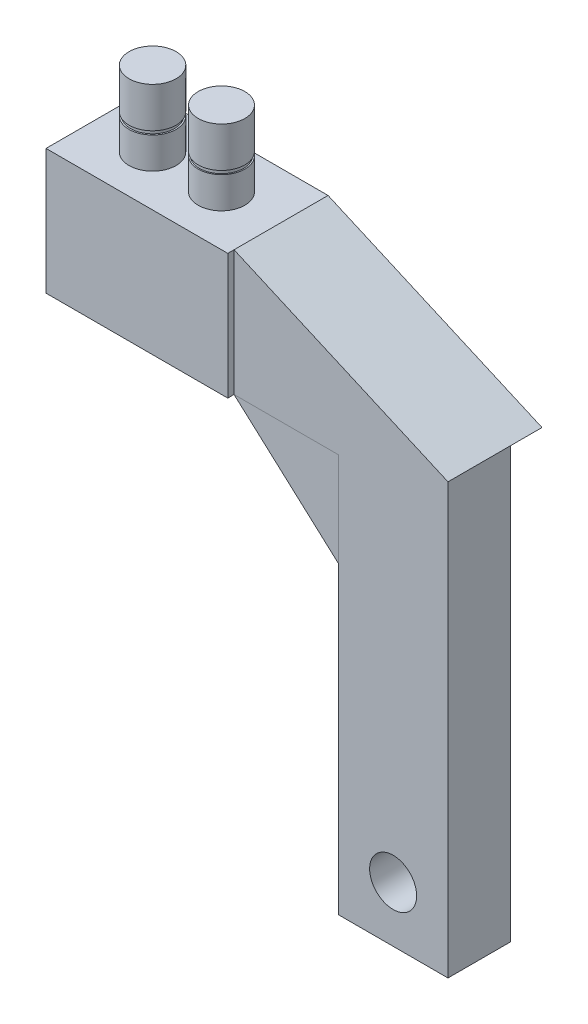
SolidWorks part; units mm, degrees
ref_plane "Front Plane" through (0, 0, 0) normal (0, 0, 1) x (1, 0, 0)
ref_plane "Top Plane" through (0, 0, 0) normal (0, 1, 0) x (1, 0, 0)
ref_plane "Right Plane" through (0, 0, 0) normal (1, 0, 0) x (0, 0, -1)
sketch "Sketch1" plane through (0, 0, 0) normal (0, 1, 0) x (1, 0, 0)
  line L1 (18.415, -10.16) -> (-18.415, -10.16)
  line L2 (18.415, -10.16) -> (18.415, 10.16)
  line L3 (18.415, 10.16) -> (-18.415, 10.16)
  line L4 (-18.415, -10.16) -> (-18.415, 10.16)
  line L5 (18.415, -10.16) -> (-18.415, 10.16) construction
  line L6 (18.415, 10.16) -> (-18.415, -10.16) construction
  point P0 (0, 0)
  dimension "D1" = 36.83
  dimension "D2" = 20.32
extrude "Boss-Extrude1" add sketch "Sketch1" against normal blind 25.4
sketch "Sketch2" plane through (18.415, 0, 0) normal (1, 0, 0) x (0, 0, -1)
  line L0 (-10.16, -25.4) -> (10.16, -25.4) construction
  line L1 (-8.89, -25.4) -> (3.81, -25.4)
  line L2 (-8.89, -25.4) -> (-8.89, -19.05)
  line L3 (-8.89, -19.05) -> (3.81, -19.05)
  line L4 (3.81, -25.4) -> (3.81, -19.05)
  line L5 (-10.16, -25.4) -> (-10.16, 0) construction
  dimension "D1" = 12.7
  dimension "D2" = 6.35
  dimension "D3" = 1.27
extrude "Boss-Extrude2" add sketch "Sketch2" along normal blind 43.3442
sketch "Sketch3" plane through (0, -25.4, 0) normal (0, -1, 0) x (-1, 0, 0)
  line L0 (-61.7592, 3.81) -> (-18.415, 3.81) construction
  line L1 (-61.7592, -8.89) -> (-39.5342, -8.89)
  line L2 (-61.7592, -8.89) -> (-61.7592, 3.81)
  line L3 (-61.7592, 3.81) -> (-39.5342, 3.81)
  line L4 (-39.5342, -8.89) -> (-39.5342, 3.81)
  dimension "D1" = 22.225
extrude "Boss-Extrude3" add sketch "Sketch3" along normal blind 80.7135
sketch "Sketch4" plane through (0, 0, 8.89) normal (0, 0, 1) x (1, 0, 0)
  line L0 (61.7592, -106.1135) -> (39.5342, -106.1135) construction
  line L1 (39.5342, -106.1135) -> (39.5342, -25.4) construction
  circle A0 centre (50.6467, -94.8842) radius 4.7625
  point P4 (0, 0)
  dimension "D1" = 11.2293
  dimension "D2" = 9.525
  dimension "D3" = 11.1125
extrude "Cut-Extrude1" cut sketch "Sketch4" against normal through all
sketch "Sketch5" plane through (0, 0, 0) normal (0, 1, 0) x (1, 0, 0)
  line L0 (-18.415, 10.16) -> (-18.415, -10.16) construction
  line L1 (18.415, 10.16) -> (-18.415, 10.16) construction
  line L2 (18.415, -10.16) -> (18.415, 10.16) construction
  circle A0 centre (-6.985, 0) radius 4.7625
  circle A1 centre (6.985, 0) radius 4.7294
  dimension "D1" = 11.43
  dimension "D3" = 9.525
  dimension "D5" = 9.4588
  dimension "D2" = 10.16
  dimension "D4" = 11.43
  dimension "D6" = 10.16
extrude "Boss-Extrude4" add sketch "Sketch5" along normal blind 15.24
sketch "Sketch7" plane through (0, 0, 10.16) normal (0, 0, 1) x (1, 0, 0)
  line L0 (18.415, 0) -> (61.7592, -19.05)
  line L1 (61.7592, -19.05) -> (18.415, -19.05)
  line L2 (18.415, -25.4) -> (18.415, 0) construction
  line L3 (18.415, -19.05) -> (18.415, 0)
  point P2 (61.4219, -17.8404)
  point P7 (62.6709, -18.9475)
  point P8 (58.3716, -18.3369)
  point P10 (0, 0)
  point P12 (0, 0)
extrude "Boss-Extrude5" add sketch "Sketch7" against normal blind 20.32
sketch "Sketch8" plane through (0, -19.05, 0) normal (0, -1, 0) x (-1, 0, 0)
  line L1 (-61.7592, -10.16) -> (-18.415, -10.16)
  line L2 (-61.7592, -10.16) -> (-61.7592, -8.89)
  line L3 (-61.7592, -8.89) -> (-18.415, -8.89)
  line L4 (-18.415, -10.16) -> (-18.415, -8.89)
extrude "Cut-Extrude2" cut sketch "Sketch8" against normal through all contours L2 L1 L4 L3
sketch "Sketch13" plane through (0, 0, 8.89) normal (0, 0, 1) x (1, 0, 0)
  line L0 (18.415, -25.4) -> (39.5342, -25.4)
  line L1 (39.5342, -25.4) -> (39.5342, -44.45)
  line L2 (39.5342, -44.45) -> (18.415, -25.4)
  line L3 (39.5342, -25.4) -> (18.415, -25.4) construction
  line L4 (39.5342, -106.1135) -> (39.5342, -25.4) construction
  point P2 (0, 0)
  dimension "D1" = 0
  dimension "D2" = 0
  dimension "D3" = 19.05
extrude "Boss-Extrude10" add sketch "Sketch13" against normal blind 20.32 separate body
sketch3d "3DSketch3"
  circle A0 centre (-6.985, 6.35, 0) radius 5.08
  circle A1 centre (6.985, 6.35, 0) radius 5.08
  circle A2 centre (-6.985, 15.24, 0) radius 4.7625 construction
  circle A3 centre (6.985, 15.24, 0) radius 4.7294 construction
  point P2 (-6.985, 11.43, 0)
  point P5 (6.985, 11.43, 0)
  point P6 (0, 0, 0)
  point P9 (-6.985, 20.0025, 0)
  point P10 (0, 0, 0)
  point P13 (6.985, 19.9694, 0)
  dimension "D2" = 10.16
  dimension "D3" = 10.16
  dimension "D1" = 6.35
extrude "Cut-Extrude4" cut sketch "3DSketch3" along direction (0, 1, 0) on the side against the normal blind 0.7366
sketch "Sketch14" plane through (0, 6.35, 0) normal (0, 1, 0) x (1, 0, 0)
  circle A0 centre (-6.985, 0) radius 4.4704
  circle A1 centre (6.985, 0) radius 4.4704
  dimension "D1" = 8.9408
  dimension "D2" = 8.9408
extrude "Boss-Extrude11" add sketch "Sketch14" along normal up to surface (0.7366 mm away) up to face at (-6.985, 7.0866, 4.7625)
